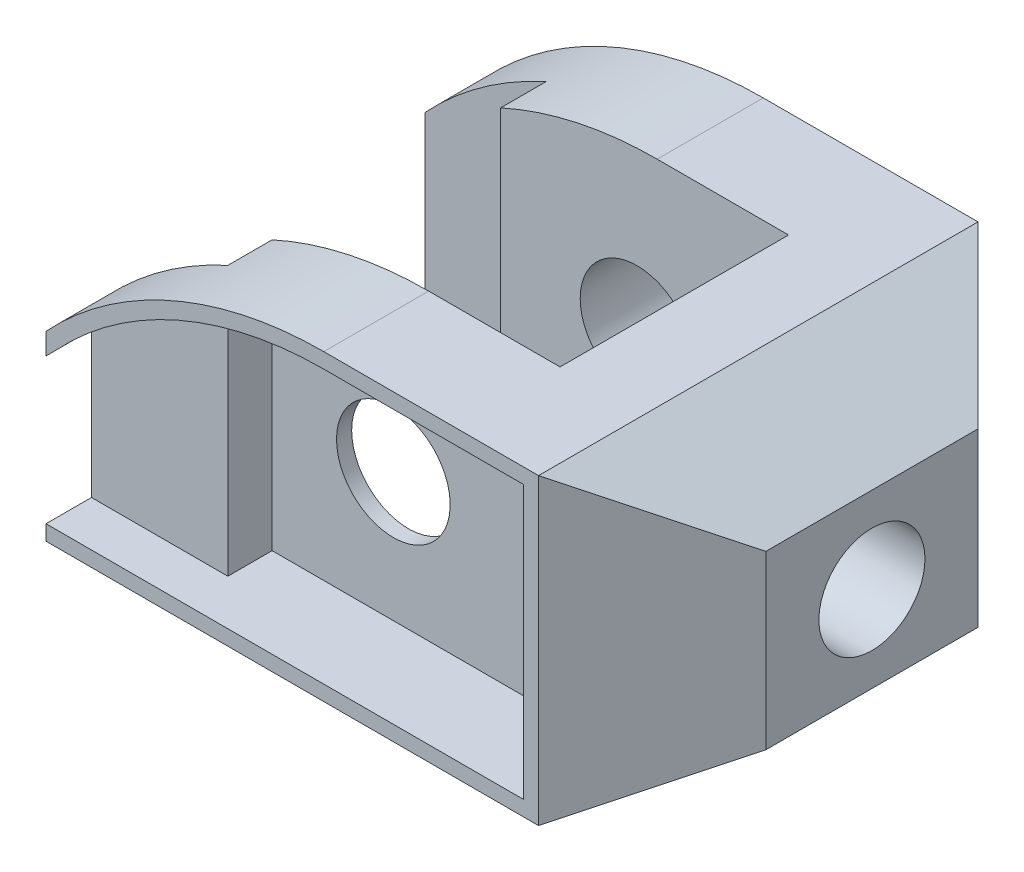
SolidWorks part; units mm, degrees
material "Alliage 1060"
ref_plane "Plan de face" through (0, 0, 0) normal (0, 0, 1) x (1, 0, 0)
ref_plane "Plan de dessus" through (0, 0, 0) normal (0, 1, 0) x (1, 0, 0)
ref_plane "Plan de droite" through (0, 0, 0) normal (1, 0, 0) x (0, 0, -1)
sketch "Esquisse1" plane through (0, 0, 0) normal (0, 0, 1) x (1, 0, 0)
  line L0 (0, 0) -> (0, 24)
  line L2 (65, 40) -> (80, 31.3397)
  line L3 (80, 31.3397) -> (80, 8.6603)
  line L4 (80, 8.6603) -> (65, 0)
  line L5 (65, 0) -> (0, 0)
  line L8 (65, 40) -> (36.6607, 40)
  line L10 (0, 24) -> (0.0424, 24.0456)
  circle A0 centre (34, 19) radius 7.5
  arc A2 (36.6607, 40) -> (0.0424, 24.0456) centre (36.6607, -10) ccw
  point P9 (12.2046, 40)
  point P10 (17.9169, 40)
  point P14 (0.4434, 24.466)
  point P15 (0, 0)
  point P16 (0, 0)
  point P17 (0, 24.0456)
  dimension "D6" = 15
  dimension "D11" = 50
  dimension "D1" = 24
  dimension "D2" = 15
  dimension "D3" = 65
  dimension "D4" = 31
  dimension "D5" = 19
  dimension "D7" = 150
  dimension "D8" = 120
  dimension "D9" = 15
  dimension "D10" = 40
extrude "Boss.-Extru.1" add sketch "Esquisse1" along normal blind 58
sketch "Esquisse2" plane through (0, 0, 0) normal (0, -1, 0) x (1, 0, 0)
sketch "Esquisse8" plane through (0, 40, 0) normal (0, 1, 0) x (1, 0, 0)
  line L0 (0, -8) -> (0.0424, -50)
  line L1 (0, -58) -> (0, 0) construction
  line L2 (0.0424, -58) -> (0.0424, 0) construction
  line L3 (0.0424, -50) -> (16.0424, -50)
  line L4 (16.0424, -50) -> (16.0424, -44)
  line L5 (16.0424, -44) -> (54, -44)
  line L6 (54, -44) -> (54, -14)
  line L7 (54, -14) -> (16, -14)
  line L8 (16, -14) -> (16, -8)
  line L9 (16, -8) -> (0, -8)
  dimension "D1" = 16
  dimension "D2" = 6
  dimension "D3" = 8
  dimension "D4" = 8
  dimension "D5" = 6
  dimension "D6" = 11
sketch "Esquisse3" plane through (16.25, -28.1458, 0) normal (0.5, -0.866, 0) x (0.866, 0.5, 0)
  line L0 (56.2917, 58) -> (73.6122, 40.6795)
  line L1 (73.6122, 58) -> (73.6122, 0) construction
  line L2 (73.6122, 40.6795) -> (73.6122, 58)
  line L3 (73.6122, 17.3205) -> (56.2917, 0)
  line L4 (56.2917, 0) -> (73.6122, 0)
  line L5 (73.6122, 0) -> (73.6122, 17.3205)
  line L6 (73.6122, 58) -> (56.2917, 58)
  dimension "D1" = 45
  dimension "D2" = 45
sketch "Esquisse4" plane through (0, 0, 0) normal (0, -1, 0) x (1, 0, 0)
  line L0 (65, 58) -> (80, 43)
  line L1 (80, 40.6795) -> (80, 58) construction
  line L2 (80, 43) -> (80, 58)
  line L3 (65, 58) -> (80, 58)
  line L4 (65, 0) -> (80, 0)
  line L5 (80, 0) -> (80, 15)
  line L6 (80, 15) -> (65, 0)
  point P11 (-24.5673, 37.6927)
  dimension "D1" = 45
  dimension "D2" = 45
extrude "Enlèv. mat.-Extru.2" cut sketch "Esquisse4" against normal through all
sketch "Esquisse5" plane through (80, 0, 0) normal (1, 0, 0) x (0, 0, -1)
  circle A0 centre (-29, 20) radius 7
  dimension "D1" = 29
  dimension "D2" = 20
extrude "Enlèv. mat.-Extru.3" cut sketch "Esquisse5" against normal through all
sketch "Esquisse6" plane through (0, 40, 0) normal (0, 1, 0) x (1, 0, 0)
  line L0 (65, 0) -> (80, 0)
  line L1 (80, 0) -> (80, -15)
  line L2 (80, -15) -> (65, 0)
sketch "Esquisse10" plane through (0, 0, 0) normal (0, -1, 0) x (1, 0, 0)
  line L0 (16.0424, 44) -> (54, 44) construction
  line L1 (16.0424, 50) -> (16.0424, 44) construction
  line L2 (54, 44) -> (54, 14) construction
  line L3 (54, 14) -> (16, 14) construction
  line L4 (16, 14) -> (16, 8) construction
  line L5 (16, 8) -> (0, 8) construction
  line L6 (0, 8) -> (0.0424, 50) construction
  line L7 (0.0424, 50) -> (16.0424, 50) construction
  line L8 (16.0424, 44) -> (54, 44)
  line L9 (16.0424, 50) -> (16.0424, 44)
  line L10 (54, 44) -> (54, 14)
  line L11 (54, 14) -> (16, 14)
  line L12 (16, 14) -> (16, 8)
  line L13 (16, 8) -> (0, 8)
  line L14 (0, 8) -> (0.0424, 50)
  line L15 (0.0424, 50) -> (16.0424, 50)
sketch "Esquisse11" plane through (0, 0, 0) normal (-1, 0, 0) x (0, 0, 1)
  line L0 (8, 0) -> (8, 40)
  line L1 (8, 0) -> (50, 0) construction
  line L2 (14, 0) -> (8, 0) construction
  line L3 (14, 40) -> (8, 40) construction
  line L4 (0, 40) -> (15, 40) construction
  line L5 (8, 40) -> (50, 40)
  line L6 (50, 40) -> (44, 40) construction
  line L7 (50, 40) -> (50, 0)
  line L8 (50, 0) -> (44, 0) construction
  line L9 (58, 0) -> (0, 0) construction
  line L10 (50, 0) -> (8, 0)
extrude "Enlèv. mat.-Extru.50" cut sketch "Esquisse11" against normal blind 16
sketch "Esquisse12" plane through (16, 0, 0) normal (-1, 0, 0) x (0, 0, 1)
  line L0 (14, 40) -> (14, 0)
  line L1 (14, 0) -> (44.1598, 0)
  line L2 (8, 0) -> (50, 0) construction
  line L3 (44.1598, 0) -> (44.1598, 40)
  line L4 (44.1598, 40) -> (14, 40)
extrude "Enlèv. mat.-Extru.51" cut sketch "Esquisse12" against normal offset from surface (38 mm away) 26 up to face at (80, 20, 22)
sketch "Esquisse13" plane through (0, 0, 58) normal (0, 0, 1) x (1, 0, 0)
  line L0 (65, 40) -> (36.6607, 40) construction
  line L1 (65, 40) -> (65, 0) construction
  line L6 (65, 40) -> (36.6607, 40)
  line L7 (65, 40) -> (65, 0)
  line L8 (0, 0) -> (65, 0) construction
  line L10 (0, 0) -> (65, 0)
  line L12 (0, 2) -> (63, 2)
  line L13 (63, 38) -> (63, 2)
  line L14 (63, 38) -> (36.6607, 38)
  line L15 (1.5072, 22.6838) -> (0, 21.1767)
  line L16 (0, 24) -> (0, 0) construction
  line L17 (0, 21.1767) -> (0, 2)
  arc A0 (36.6607, 40) -> (0.0424, 24.0456) centre (36.6607, -10) ccw construction
  arc A1 (36.6607, 40) -> (0.0424, 24.0456) centre (36.6607, -10) ccw
  arc A2 (36.6607, 38) -> (1.5072, 22.6838) centre (36.6607, -10) ccw
  line M15 (0, 24) -> (0, 0)
  circle M17 centre (34, 19) radius 7.5
  dimension "D1" = 2
extrude "Enlèv. mat.-Extru.52" cut sketch "Esquisse13" against normal offset from surface (6 mm away) 2 contours L14 A2 L15 L12 L13 M15 M17 up to face at (6.2945, 16.8739, 50)
sketch "Esquisse14" plane through (0, 0, 52) normal (0, 0, 1) x (1, 0, 0)
  line L1 (63, 38) -> (63, 2) construction
  line L2 (63, 2) -> (0, 2) construction
  line L3 (63, 38) -> (36.6607, 38) construction
  line L5 (63, 38) -> (63, 2)
  line L6 (63, 2) -> (18, 2)
  line L7 (63, 38) -> (36.6607, 38)
  line L8 (18, 2) -> (18, 34.2242)
  arc A0 (36.6607, 38) -> (1.5072, 22.6838) centre (36.6607, -10) ccw construction
  arc A1 (36.6607, 38) -> (18, 34.2242) centre (36.6607, -10) ccw
extrude "Enlèv. mat.-Extru.53" cut sketch "Esquisse14" against normal offset from surface (5.8402 mm away) 2 contours L5 L6 L8 A1 L7 up to face at (41.5, 19, 44.1598)
equation "\"A\"= 58"
equation "\"B\"= 40"
equation "\"C\"= 65"
